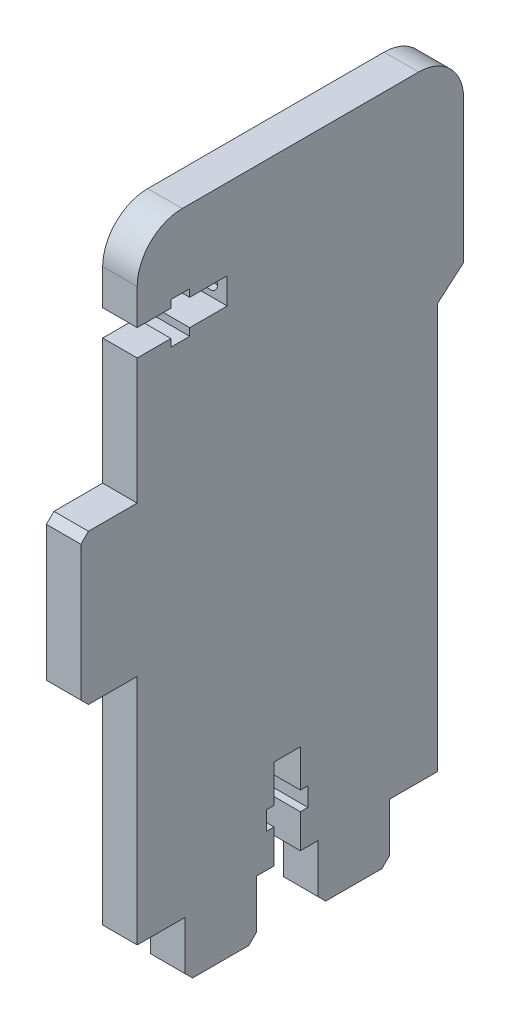
SolidWorks part; units mm, degrees
ref_plane "Front Plane" through (0, 0, 0) normal (0, 0, 1) x (1, 0, 0)
ref_plane "Top Plane" through (0, 0, 0) normal (0, 1, 0) x (1, 0, 0)
ref_plane "Right Plane" through (0, 0, 0) normal (1, 0, 0) x (0, 0, -1)
sketch "Sketch1" plane through (0, 0, 0) normal (1, 0, 0) x (0, 0, -1)
  line L0 (28.3516, 12.3874) -> (28.3516, 5.8874)
  line L1 (28.3516, 5.8874) -> (27.3516, 4.8874)
  line L2 (27.3516, 4.8874) -> (19.8516, 4.8874)
  line L3 (19.8516, 4.8874) -> (18.8516, 5.8874)
  line L4 (18.8516, 5.8874) -> (18.8516, 12.3874)
  line L5 (18.8516, 12.3874) -> (12.4766, 12.3874)
  line L6 (12.4766, 12.3874) -> (12.4766, 43.3874)
  line L7 (12.4766, 43.3874) -> (5.9766, 43.3874)
  line L8 (5.9766, 43.3874) -> (4.9766, 44.3874)
  line L9 (4.9766, 44.3874) -> (4.9766, 62.3874)
  line L10 (4.9766, 62.3874) -> (5.9766, 63.3874)
  line L11 (5.9766, 63.3874) -> (12.4766, 63.3874)
  line L12 (12.4766, 63.3874) -> (12.4766, 80.1374)
  line L13 (12.4766, 80.1374) -> (16.9766, 80.1374)
  line L14 (16.9766, 80.1374) -> (16.9766, 79.1374)
  line L15 (16.9766, 79.1374) -> (19.4766, 79.1374)
  line L16 (19.4766, 79.1374) -> (19.4766, 80.1374)
  line L17 (19.4766, 80.1374) -> (24.4766, 80.1374)
  line L18 (24.4766, 80.1374) -> (24.4766, 83.6374)
  line L19 (24.4766, 83.6374) -> (19.4766, 83.6374)
  line L20 (19.4766, 83.6374) -> (19.4766, 84.6374)
  line L21 (19.4766, 84.6374) -> (16.9766, 84.6374)
  line L22 (16.9766, 84.6374) -> (16.9766, 83.6374)
  line L23 (16.9766, 83.6374) -> (12.4766, 83.6374)
  line L24 (12.4766, 83.6374) -> (12.4766, 88.3874)
  line L25 (18.4766, 94.3874) -> (49.9766, 94.3874)
  line L26 (55.9766, 88.3874) -> (55.9766, 69.3874)
  line L27 (55.9766, 69.3874) -> (52.4766, 66.3874)
  line L28 (52.4766, 66.3874) -> (52.4766, 12.3874)
  line L29 (52.4766, 12.3874) -> (46.1016, 12.3874)
  line L30 (46.1016, 12.3874) -> (46.1016, 5.8874)
  line L31 (46.1016, 5.8874) -> (45.1016, 4.8874)
  line L32 (45.1016, 4.8874) -> (37.6016, 4.8874)
  line L33 (37.6016, 4.8874) -> (36.6016, 5.8874)
  line L34 (36.6016, 5.8874) -> (36.6016, 12.3874)
  line L35 (36.6016, 12.3874) -> (34.2266, 12.3874)
  line L36 (34.2266, 12.3874) -> (34.2266, 16.8874)
  line L37 (34.2266, 16.8874) -> (35.2266, 16.8874)
  line L38 (35.2266, 16.8874) -> (35.2266, 19.3874)
  line L39 (35.2266, 19.3874) -> (34.2266, 19.3874)
  line L40 (34.2266, 19.3874) -> (34.2266, 24.3874)
  line L41 (34.2266, 24.3874) -> (30.7266, 24.3874)
  line L42 (30.7266, 24.3874) -> (30.7266, 19.3874)
  line L43 (30.7266, 19.3874) -> (29.7266, 19.3874)
  line L44 (29.7266, 19.3874) -> (29.7266, 16.8874)
  line L45 (29.7266, 16.8874) -> (30.7266, 16.8874)
  line L46 (30.7266, 16.8874) -> (30.7266, 12.3874)
  line L47 (30.7266, 12.3874) -> (28.3516, 12.3874)
  arc A0 (18.4766, 94.3874) -> (12.4766, 88.3874) centre (18.4766, 88.3874) ccw
  arc A1 (55.9766, 88.3874) -> (49.9766, 94.3874) centre (49.9766, 88.3874) ccw
extrude "Extrude1" add sketch "Sketch1" along normal blind 4.6
sketch "Sketch2" plane through (0, 0, -24.4766) normal (0, 0, 1) x (1, 0, 0)
  line L0 (0, 83.6374) -> (4.6, 80.1374)
  circle A0 centre (2.3, 81.8874) radius 1
  dimension "D1" = 2
extrude "Extrude2" cut sketch "Sketch2" against normal blind 1 contours A0
sketch "Sketch3" plane through (0, 24.3874, 0) normal (0, -1, 0) x (1, 0, 0)
  line L0 (0, -30.7266) -> (4.6, -34.2266)
  circle A0 centre (2.3, -32.4766) radius 1
  dimension "D1" = 2
extrude "Extrude3" cut sketch "Sketch3" against normal blind 1 contours A0
